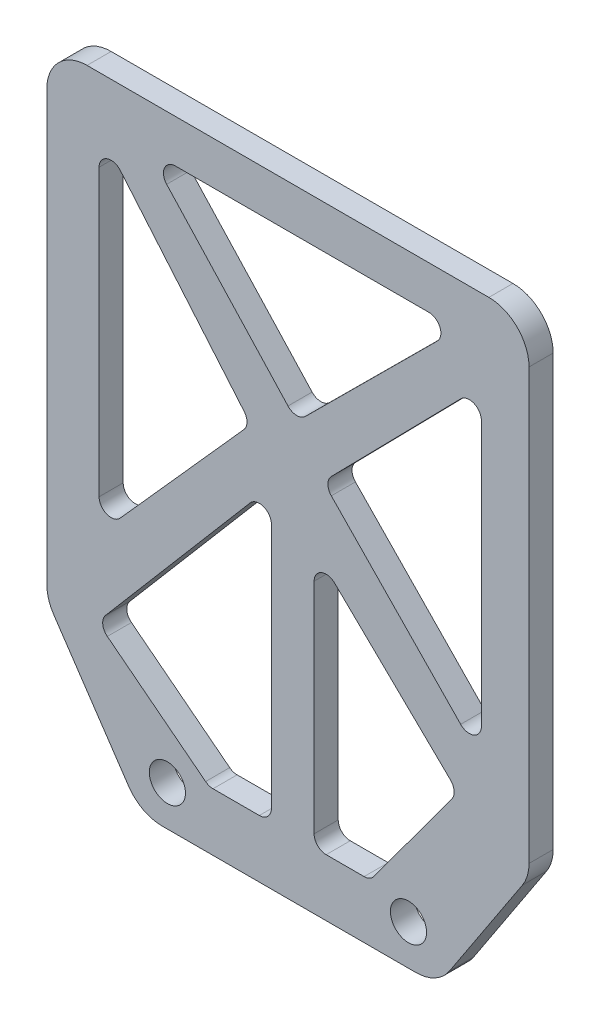
SolidWorks part; units mm, degrees
material "ABS"
ref_plane "前视基准面" through (0, 0, 0) normal (0, 0, 1) x (1, 0, 0)
ref_plane "上视基准面" through (0, 0, 0) normal (0, 1, 0) x (1, 0, 0)
ref_plane "右视基准面" through (0, 0, 0) normal (1, 0, 0) x (0, 0, -1)
sketch "草图1" plane through (0, 0, 0) normal (0, 0, 1) x (1, 0, 0)
  line L1 (0, 0) -> (60, 0)
  line L2 (0, 0) -> (0, 77.3)
  line L3 (0, 77.3) -> (60, 77.3)
  line L4 (60, 0) -> (60, 77.3)
  circle A0 centre (15, 5) radius 2.25
  circle A1 centre (45, 5) radius 2.25
  dimension "D3" = 5
  dimension "D4" = 4.5
  dimension "D5" = 5
  dimension "D6" = 4.5
  dimension "D7" = 15
  dimension "D8" = 15
  dimension "D1" = 60
  dimension "D2" = 77.3
extrude "凸台-拉伸1" add sketch "草图1" along normal blind 3
sketch "草图2" plane through (0, 0, 3) normal (0, 0, 1) x (1, 0, 0)
  line L0 (60, 0) -> (60, 77.3) construction
  line L1 (0, 77.3) -> (60, 77.3) construction
  line L2 (0, 77.3) -> (0, 17.3) construction
  line L3 (0, 17.3) -> (60, 17.3) construction
  line L4 (60, 77.3) -> (60, 17.3) construction
  line L10 (6.4981, 71.1774) -> (25.3901, 48.7914)
  line L11 (25.3901, 48.7914) -> (6.4981, 27.6294)
  line L12 (6.4981, 27.6294) -> (6.4981, 71.1774)
  line L13 (12.5806, 71.9561) -> (51.1658, 71.9561)
  line L14 (51.1658, 71.9561) -> (31.0618, 51.9547)
  line L15 (31.0618, 51.9547) -> (12.5806, 71.9561)
  line L16 (54.0682, 67.2352) -> (34.3754, 47.1615)
  line L17 (34.3754, 47.1615) -> (54.0682, 26.8854)
  line L18 (54.0682, 26.8854) -> (54.0682, 67.2352)
  line L19 (27.9386, 43.3997) -> (6.2873, 17.9867)
  line L20 (6.2873, 17.9867) -> (20.1604, 7.1844)
  line L21 (20.1604, 7.1844) -> (27.9386, 7.1844)
  line L22 (27.9386, 7.1844) -> (27.9386, 43.3997)
  line L23 (33.2563, 39.3933) -> (33.2563, 7.1193)
  line L24 (33.2563, 7.1193) -> (40.2353, 7.1193)
  line L25 (40.2353, 7.1193) -> (51.1658, 21.9992)
  line L26 (51.1658, 21.9992) -> (33.2563, 39.3933)
  line L27 (0, 17.3) -> (11.6657, 0)
  line L28 (0, 0) -> (60, 0) construction
  line L29 (11.6657, 0) -> (0, 0)
  line L30 (0, 0) -> (0, 17.3)
  line L31 (60, 17.3) -> (48.6174, 0)
  line L32 (48.6174, 0) -> (60, 0)
  line L33 (60, 0) -> (60, 17.3)
  point P27 (33.2563, 39.3933)
  point P28 (6.4981, 71.1774)
  point P29 (11.6657, 0)
  point P30 (20.1604, 7.1844)
  dimension "D1" = 60
extrude "切除-拉伸1" cut sketch "草图2" against normal through all
fillet "圆角2" radius 1.5 17 edges at (27.9386, 7.1844, 1.5) (20.1604, 7.1844, 1.5) (6.2873, 17.9867, 1.5) (27.9386, 43.3997, 1.5) (54.0682, 26.8854, 1.5) (34.3754, 47.1615, 1.5) (54.0682, 67.2352, 1.5) (33.2563, 7.1193, 1.5) (33.2563, 39.3933, 1.5) (51.1658, 21.9992, 1.5) (40.2353, 7.1193, 1.5) (6.4981, 71.1774, 1.5) (25.3901, 48.7914, 1.5) (6.4981, 27.6294, 1.5) (12.5806, 71.9561, 1.5) (51.1658, 71.9561, 1.5) (31.0618, 51.9547, 1.5)
fillet "圆角3" radius 5 6 edges at (60, 77.3, 1.5) (60, 17.3, 1.5) (48.6174, 0, 1.5) (11.6657, 0, 1.5) (0, 17.3, 1.5) (0, 77.3, 1.5)
